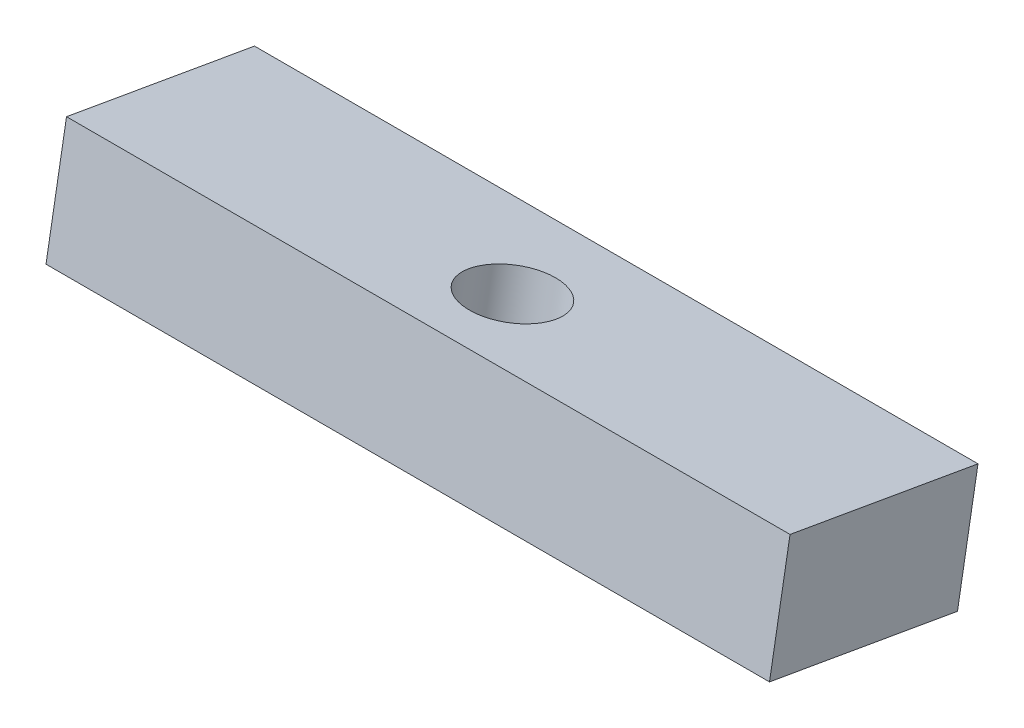
SolidWorks part; units mm, degrees
ref_plane "Front Plane" through (0, 0, 0) normal (0, 0, 1) x (1, 0, 0)
ref_plane "Top Plane" through (0, 0, 0) normal (0, 1, 0) x (1, 0, 0)
ref_plane "Right Plane" through (0, 0, 0) normal (1, 0, 0) x (0, 0, -1)
sketch "Sketch1" plane through (0, 182.8877, -31.9321) normal (0, -0.9851, 0.172) x (1, 0, 0)
  line L0 (-11.8, -70.8649) -> (-1.3, -70.8649) construction
  line L1 (-6, -66.0649) -> (-1.3, -66.0649) construction
  line L2 (-11.8, -66.0649) -> (-7.1, -66.0649) construction
  line L3 (-15.65, -70.8649) -> (2.55, -70.8649)
  line L4 (-6, -66.0649) -> (2.55, -66.0649)
  line L5 (-15.65, -66.0649) -> (-7.1, -66.0649)
  line L6 (-15.65, 16.6351) -> (-15.65, -99.3649) construction
  line L7 (2.55, 16.6351) -> (2.55, -99.3649) construction
  line L8 (-15.65, -66.0649) -> (-15.65, -70.8649)
  line L9 (2.55, -66.0649) -> (2.55, -70.8649)
  line L10 (-7.1, -66.0649) -> (-6, -66.0649)
  circle A0 centre (-6.55, -68.2149) radius 1.1
extrude "Boss-Extrude1" add sketch "Sketch1" along normal blind 3
